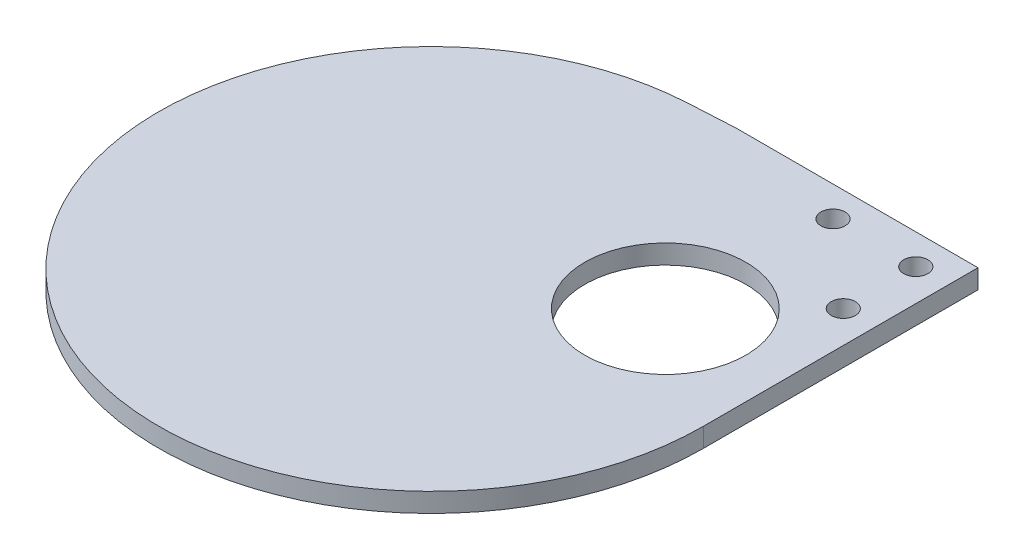
SolidWorks part; units mm, degrees
ref_plane "Front" through (0, 0, 0) normal (0, 0, 1) x (1, 0, 0)
ref_plane "Top" through (0, 0, 0) normal (0, 1, 0) x (1, 0, 0)
ref_plane "Right" through (0, 0, 0) normal (1, 0, 0) x (0, 0, -1)
sketch "Sketch1" plane through (0, 0, 0) normal (0, 1, 0) x (1, 0, 0)
  line L0 (0, 0) -> (0, 31.75) construction
  line L1 (20, 31.75) -> (-20, 31.75) construction
  line L2 (-20, 31.75) -> (-27.5726, 31.3315)
  line L3 (20, 31.75) -> (20, -13.6848)
  line L4 (20, 31.75) -> (-20, 31.75)
  circle A0 centre (0, 0) radius 13.335
  arc A1 (-27.5726, 31.3315) -> (20, -13.6848) centre (-25.085, -13.6848) ccw
  circle A2 centre (-25.085, -13.6848) radius 41.91 construction
  circle A4 centre (-25.085, -13.6848) radius 11 construction
  circle A9 centre (-25.085, -13.6848) radius 45.085 construction
  point P23 (-24.0872, -15.3733)
  dimension "D1" = 26.67
  dimension "D4" = 90.17
  dimension "D7" = 22
  dimension "D2" = 31.75
  dimension "D3" = 40
  dimension "D5" = 3.175
extrude "Boss-Extrude1" add sketch "Sketch1" along normal blind 3.175
sketch "Sketch2" plane through (0, 0, 0) normal (0, -1, 0) x (1, 0, 0)
  circle A0 centre (14.706, -14.75) radius 2
  circle A1 centre (14.706, -26.75) radius 2
  circle A2 centre (1, -26.75) radius 2
  dimension "D1" = 4
extrude "Cut-Extrude1" cut sketch "Sketch2" against normal up to next
